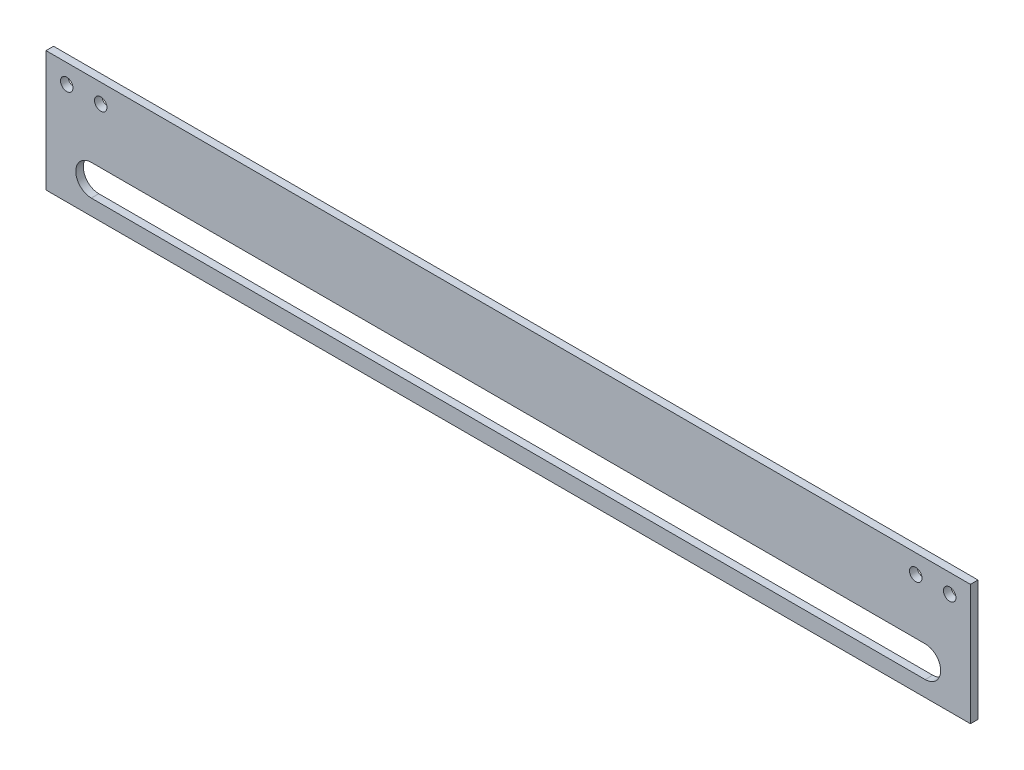
SolidWorks part; units mm, degrees
ref_plane "前视基准面" through (0, 0, 0) normal (0, 0, 1) x (1, 0, 0)
ref_plane "上视基准面" through (0, 0, 0) normal (0, 1, 0) x (1, 0, 0)
ref_plane "右视基准面" through (0, 0, 0) normal (1, 0, 0) x (0, 0, -1)
sketch "草图1" plane through (0, 0, 0) normal (0, 0, 1) x (1, 0, 0)
  line L0 (12, 8.25) -> (233, 8.25) construction
  line L1 (0, 0) -> (245, 0)
  line L2 (0, 0) -> (0, 32)
  line L3 (0, 32) -> (245, 32)
  line L4 (245, 0) -> (245, 32)
  line L5 (12, 12.35) -> (233, 12.35)
  line L6 (12, 4.15) -> (233, 4.15)
  line L7 (122.5, 32) -> (122.5, 36.1029)
  line L8 (10, 32) -> (10, 0) construction
  arc A0 (12, 12.35) -> (12, 4.15) centre (12, 8.25) ccw
  arc A1 (233, 4.15) -> (233, 12.35) centre (233, 8.25) ccw
  circle A2 centre (14.5, 27) radius 1.65
  circle A3 centre (5.5, 27) radius 1.65
  circle A4 centre (230.5, 27) radius 1.65
  circle A5 centre (239.5, 27) radius 1.65
  point P7 (122.5, 8.25)
  dimension "D4" = 4.1
  dimension "D6" = 9
  dimension "D7" = 3.3
  dimension "D1" = 245
  dimension "D2" = 8.25
  dimension "D3" = 32
  dimension "D5" = 12
  dimension "D8" = 5
  dimension "D9" = 10
extrude "凸台-拉伸1" add sketch "草图1" along normal blind 2
